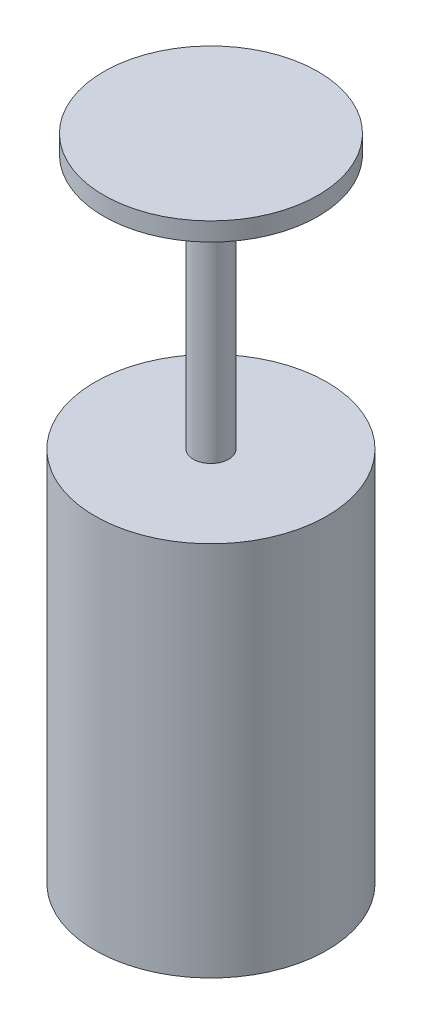
SolidWorks part; units mm, degrees
ref_plane "Front Plane" through (0, 0, 0) normal (0, 0, 1) x (1, 0, 0)
ref_plane "Top Plane" through (0, 0, 0) normal (0, 1, 0) x (1, 0, 0)
ref_plane "Right Plane" through (0, 0, 0) normal (1, 0, 0) x (0, 0, -1)
sketch "Sketch1" plane through (0, 0, 0) normal (0, 0, 1) x (1, 0, 0)
  line L1 (0, 0) -> (16.0655, 0)
  line L2 (0, 0) -> (0, -52.07)
  line L3 (0, -52.07) -> (16.0655, -52.07)
  line L4 (16.0655, 0) -> (16.0655, -52.07)
  line L5 (0, 0) -> (2.4506, 0)
  line L6 (0, 0) -> (0, 35.306)
  line L7 (0, 35.306) -> (2.4506, 35.306)
  line L8 (2.4506, 0) -> (2.4506, 35.306)
  line L9 (0, 35.306) -> (14.8364, 35.306)
  line L10 (0, 35.306) -> (0, 37.846)
  line L11 (0, 37.846) -> (14.8364, 37.846)
  line L12 (14.8364, 35.306) -> (14.8364, 37.846)
  dimension "D1" = 16.0655
  dimension "D2" = 52.07
  dimension "D3" = 89.916
  dimension "D4" = 2.54
revolve "Revolve1" add sketch "Sketch1" angle 360 about L6
